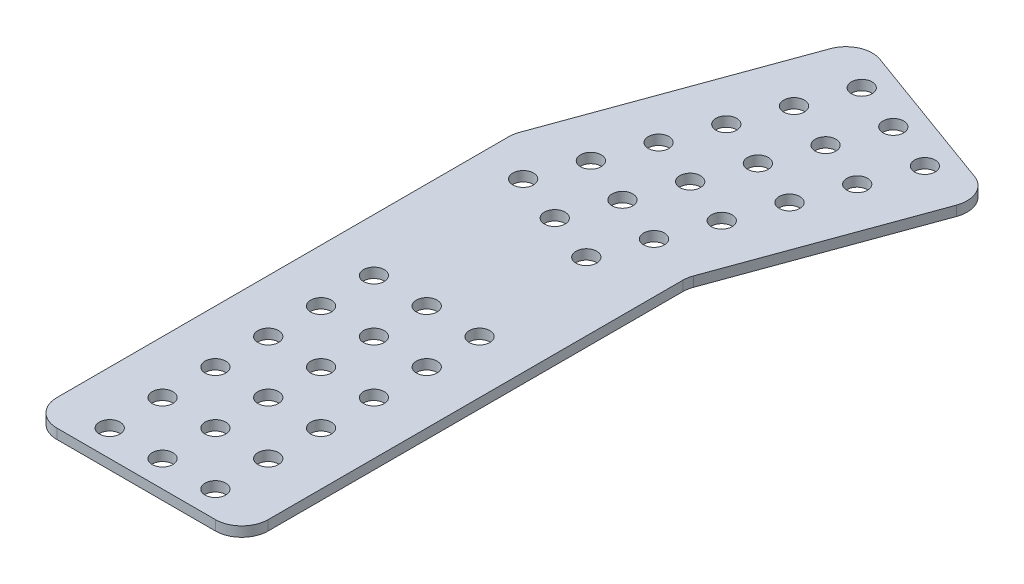
SolidWorks part; units mm, degrees
ref_plane "Front Plane" through (0, 0, 0) normal (0, 0, 1) x (1, 0, 0)
ref_plane "Top Plane" through (0, 0, 0) normal (0, 1, 0) x (1, 0, 0)
ref_plane "Right Plane" through (0, 0, 0) normal (1, 0, 0) x (0, 0, -1)
sketch "Sketch1" plane through (0, 0, 0) normal (0, 1, 0) x (1, 0, 0)
  line L0 (-80.3795, -295.1056) -> (-128.1159, -277.731) construction
  line L1 (-80.3795, -295.1056) -> (128.1159, 277.731) construction
  line L2 (-124.5455, -267.9214) -> (80.3795, 295.1056) construction
  line L3 (128.1159, 277.731) -> (80.3795, 295.1056) construction
  line L4 (-80.3795, -295.1056) -> (80.3795, 295.1056) construction
  line L5 (-128.1159, -277.731) -> (128.1159, 277.731) construction
  line L6 (104.2477, 286.4183) -> (-104.2477, -286.4183) construction
  line L7 (-73.7455, -307.8056) -> (-124.5455, -307.8056)
  line L8 (-73.7455, -307.8056) -> (-73.7455, -422.1056) construction
  line L9 (-73.7455, -422.1056) -> (-124.5455, -422.1056) construction
  line L10 (-124.5455, -307.8056) -> (-124.5455, -422.1056) construction
  line L11 (-99.1455, -307.8056) -> (-99.1455, -422.1056) construction
  line L12 (-105.4955, -307.8056) -> (-105.4955, -422.1056) construction
  line L13 (-99.1455, -307.8056) -> (-99.1455, -288.2754) construction
  line L14 (98.2807, 288.5901) -> (-110.2148, -284.2465) construction
  line L15 (-102.054, -206.1264) -> (-54.3176, -223.501)
  line L16 (-102.054, -206.1264) -> (-124.5455, -267.9214)
  line L19 (-73.7455, -384.0056) -> (-124.5455, -384.0056)
  line L20 (-73.7455, -307.8056) -> (-73.7455, -384.0056)
  line L21 (-124.5455, -307.8056) -> (-124.5455, -384.0056)
  line L22 (-124.5455, -307.8056) -> (-124.5455, -267.9214)
  line L23 (-124.5455, -267.9214) -> (-73.7455, -286.4111)
  line L24 (-73.7455, -307.8056) -> (-73.7455, -286.4111)
  line L26 (-128.1159, -277.731) -> (-124.5455, -307.8056) construction
  line L27 (-73.7455, -286.4111) -> (-73.7455, -276.8788)
  line L28 (-54.3176, -223.501) -> (-73.7455, -276.8788)
  circle A0 centre (-111.8455, -314.1556) radius 2.4892
  circle A1 centre (-111.8455, -326.8556) radius 2.4892
  circle A2 centre (-111.8455, -339.5556) radius 2.4892
  circle A3 centre (-111.8455, -352.2556) radius 2.4892
  circle A4 centre (-111.8455, -364.9556) radius 2.4892
  circle A5 centre (-111.8455, -377.6556) radius 2.4892
  circle A6 centre (-111.8455, -390.3556) radius 2.4892 construction
  circle A7 centre (-111.8455, -403.0556) radius 2.4892 construction
  circle A8 centre (-111.8455, -415.7556) radius 2.4892 construction
  circle A9 centre (-99.1455, -403.0556) radius 2.4892 construction
  circle A10 centre (-99.1455, -390.3556) radius 2.4892 construction
  circle A11 centre (-99.1455, -377.6556) radius 2.4892
  circle A12 centre (-99.1455, -364.9556) radius 2.4892
  circle A13 centre (-99.1455, -352.2556) radius 2.4892
  circle A14 centre (-99.1455, -339.5556) radius 2.4892
  circle A15 centre (-99.1455, -326.8556) radius 2.4892
  circle A16 centre (-99.1455, -314.1556) radius 2.4892
  circle A17 centre (-86.4455, -415.7556) radius 2.4892 construction
  circle A18 centre (-86.4455, -403.0556) radius 2.4892 construction
  circle A19 centre (-86.4455, -390.3556) radius 2.4892 construction
  circle A20 centre (-86.4455, -377.6556) radius 2.4892
  circle A21 centre (-86.4455, -364.9556) radius 2.4892
  circle A22 centre (-86.4455, -352.2556) radius 2.4892
  circle A23 centre (-86.4455, -339.5556) radius 2.4892
  circle A24 centre (-86.4455, -326.8556) radius 2.4892
  circle A25 centre (-86.4455, -314.1556) radius 2.4892
  circle A26 centre (-99.1455, -415.7556) radius 2.4892 construction
  circle A27 centre (90.1418, 284.7949) radius 2.4892 construction
  circle A28 centre (85.7982, 272.8608) radius 2.4892 construction
  circle A29 centre (81.4545, 260.9267) radius 2.4892 construction
  circle A30 centre (77.1108, 248.9926) radius 2.4892 construction
  circle A31 centre (72.7672, 237.0585) radius 2.4892 construction
  circle A32 centre (68.4235, 225.1244) radius 2.4892 construction
  circle A33 centre (64.0799, 213.1903) radius 2.4892 construction
  circle A34 centre (59.7362, 201.2562) radius 2.4892 construction
  circle A35 centre (55.3926, 189.3221) radius 2.4892 construction
  circle A36 centre (51.0489, 177.3881) radius 2.4892 construction
  circle A37 centre (46.7053, 165.454) radius 2.4892 construction
  circle A38 centre (42.3616, 153.5199) radius 2.4892 construction
  circle A39 centre (38.0179, 141.5858) radius 2.4892 construction
  circle A40 centre (33.6743, 129.6517) radius 2.4892 construction
  circle A41 centre (29.3306, 117.7176) radius 2.4892 construction
  circle A42 centre (24.987, 105.7835) radius 2.4892 construction
  circle A43 centre (20.6433, 93.8494) radius 2.4892 construction
  circle A44 centre (16.2997, 81.9153) radius 2.4892 construction
  circle A45 centre (11.956, 69.9812) radius 2.4892 construction
  circle A46 centre (7.6124, 58.0471) radius 2.4892 construction
  circle A47 centre (3.2687, 46.113) radius 2.4892 construction
  circle A48 centre (-1.075, 34.1789) radius 2.4892 construction
  circle A49 centre (-5.4186, 22.2448) radius 2.4892 construction
  circle A50 centre (-9.7623, 10.3107) radius 2.4892 construction
  circle A51 centre (-14.1059, -1.6234) radius 2.4892 construction
  circle A52 centre (-18.4496, -13.5575) radius 2.4892 construction
  circle A53 centre (-22.7932, -25.4916) radius 2.4892 construction
  circle A54 centre (-27.1369, -37.4257) radius 2.4892 construction
  circle A55 centre (-31.4805, -49.3598) radius 2.4892 construction
  circle A56 centre (-35.8242, -61.2939) radius 2.4892 construction
  circle A57 centre (-40.1679, -73.228) radius 2.4892 construction
  circle A58 centre (-44.5115, -85.1621) radius 2.4892 construction
  circle A59 centre (-48.8552, -97.0962) radius 2.4892 construction
  circle A60 centre (-53.1988, -109.0303) radius 2.4892 construction
  circle A61 centre (-57.5425, -120.9644) radius 2.4892 construction
  circle A62 centre (-61.8861, -132.8985) radius 2.4892 construction
  circle A63 centre (-66.2298, -144.8325) radius 2.4892 construction
  circle A64 centre (-70.5734, -156.7666) radius 2.4892 construction
  circle A65 centre (-74.9171, -168.7007) radius 2.4892 construction
  circle A66 centre (-79.2608, -180.6348) radius 2.4892 construction
  circle A67 centre (-83.6044, -192.5689) radius 2.4892 construction
  circle A68 centre (-87.9481, -204.503) radius 2.4892 construction
  circle A69 centre (-92.2917, -216.4371) radius 2.4892
  circle A70 centre (-96.6354, -228.3712) radius 2.4892
  circle A71 centre (-100.979, -240.3053) radius 2.4892
  circle A72 centre (-105.3227, -252.2394) radius 2.4892
  circle A73 centre (-109.6664, -264.1735) radius 2.4892
  circle A74 centre (-114.01, -276.1076) radius 2.4892
  circle A75 centre (62.983, 173.0444) radius 2.4892 construction
  circle A76 centre (67.3267, 184.9785) radius 2.4892 construction
  circle A77 centre (71.6703, 196.9126) radius 2.4892 construction
  circle A78 centre (76.014, 208.8467) radius 2.4892 construction
  circle A79 centre (80.3576, 220.7808) radius 2.4892 construction
  circle A80 centre (84.7013, 232.7149) radius 2.4892 construction
  circle A81 centre (89.0449, 244.649) radius 2.4892 construction
  circle A82 centre (93.3886, 256.5831) radius 2.4892 construction
  circle A83 centre (97.7323, 268.5172) radius 2.4892 construction
  circle A84 centre (102.0759, 280.4513) radius 2.4892 construction
  circle A85 centre (-102.0759, -280.4513) radius 2.4892
  circle A86 centre (-97.7323, -268.5172) radius 2.4892
  circle A87 centre (-93.3886, -256.5831) radius 2.4892
  circle A88 centre (-89.0449, -244.649) radius 2.4892
  circle A89 centre (-84.7013, -232.7149) radius 2.4892
  circle A90 centre (-80.3576, -220.7808) radius 2.4892
  circle A91 centre (-76.014, -208.8467) radius 2.4892 construction
  circle A92 centre (-71.6703, -196.9126) radius 2.4892 construction
  circle A93 centre (-67.3267, -184.9785) radius 2.4892 construction
  circle A94 centre (-62.983, -173.0444) radius 2.4892 construction
  circle A95 centre (-58.6394, -161.1103) radius 2.4892 construction
  circle A96 centre (-54.2957, -149.1762) radius 2.4892 construction
  circle A97 centre (-49.952, -137.2421) radius 2.4892 construction
  circle A98 centre (-45.6084, -125.308) radius 2.4892 construction
  circle A99 centre (-41.2647, -113.3739) radius 2.4892 construction
  circle A100 centre (-36.9211, -101.4398) radius 2.4892 construction
  circle A101 centre (-32.5774, -89.5057) radius 2.4892 construction
  circle A102 centre (-28.2338, -77.5716) radius 2.4892 construction
  circle A103 centre (-23.8901, -65.6375) radius 2.4892 construction
  circle A104 centre (-19.5465, -53.7034) radius 2.4892 construction
  circle A105 centre (-15.2028, -41.7693) radius 2.4892 construction
  circle A106 centre (-10.8591, -29.8352) radius 2.4892 construction
  circle A107 centre (-6.5155, -17.9011) radius 2.4892 construction
  circle A108 centre (-2.1718, -5.967) radius 2.4892 construction
  circle A109 centre (2.1718, 5.967) radius 2.4892 construction
  circle A110 centre (6.5155, 17.9011) radius 2.4892 construction
  circle A111 centre (10.8591, 29.8352) radius 2.4892 construction
  circle A112 centre (15.2028, 41.7693) radius 2.4892 construction
  circle A113 centre (19.5465, 53.7034) radius 2.4892 construction
  circle A114 centre (23.8901, 65.6375) radius 2.4892 construction
  circle A115 centre (28.2338, 77.5716) radius 2.4892 construction
  circle A116 centre (32.5774, 89.5057) radius 2.4892 construction
  circle A117 centre (36.9211, 101.4398) radius 2.4892 construction
  circle A118 centre (41.2647, 113.3739) radius 2.4892 construction
  circle A119 centre (45.6084, 125.308) radius 2.4892 construction
  circle A120 centre (49.952, 137.2421) radius 2.4892 construction
  circle A121 centre (54.2957, 149.1762) radius 2.4892 construction
  circle A122 centre (58.6394, 161.1103) radius 2.4892 construction
  circle A123 centre (-90.1418, -284.7949) radius 2.4892
  circle A124 centre (-85.7982, -272.8608) radius 2.4892
  circle A125 centre (-81.4545, -260.9267) radius 2.4892
  circle A126 centre (-77.1108, -248.9926) radius 2.4892
  circle A127 centre (-72.7672, -237.0585) radius 2.4892
  circle A128 centre (-68.4235, -225.1244) radius 2.4892
  circle A129 centre (-64.0799, -213.1903) radius 2.4892 construction
  circle A130 centre (-59.7362, -201.2562) radius 2.4892 construction
  circle A131 centre (-55.3926, -189.3221) radius 2.4892 construction
  circle A132 centre (-51.0489, -177.3881) radius 2.4892 construction
  circle A133 centre (-46.7053, -165.454) radius 2.4892 construction
  circle A134 centre (-42.3616, -153.5199) radius 2.4892 construction
  circle A135 centre (-38.0179, -141.5858) radius 2.4892 construction
  circle A136 centre (-33.6743, -129.6517) radius 2.4892 construction
  circle A137 centre (-29.3306, -117.7176) radius 2.4892 construction
  circle A138 centre (-24.987, -105.7835) radius 2.4892 construction
  circle A139 centre (-20.6433, -93.8494) radius 2.4892 construction
  circle A140 centre (-16.2997, -81.9153) radius 2.4892 construction
  circle A141 centre (-11.956, -69.9812) radius 2.4892 construction
  circle A142 centre (-7.6124, -58.0471) radius 2.4892 construction
  circle A143 centre (-3.2687, -46.113) radius 2.4892 construction
  circle A144 centre (1.075, -34.1789) radius 2.4892 construction
  circle A145 centre (5.4186, -22.2448) radius 2.4892 construction
  circle A146 centre (9.7623, -10.3107) radius 2.4892 construction
  circle A147 centre (14.1059, 1.6234) radius 2.4892 construction
  circle A148 centre (18.4496, 13.5575) radius 2.4892 construction
  circle A149 centre (22.7932, 25.4916) radius 2.4892 construction
  circle A150 centre (27.1369, 37.4257) radius 2.4892 construction
  circle A151 centre (31.4805, 49.3598) radius 2.4892 construction
  circle A152 centre (35.8242, 61.2939) radius 2.4892 construction
  circle A153 centre (40.1679, 73.228) radius 2.4892 construction
  circle A154 centre (44.5115, 85.1621) radius 2.4892 construction
  circle A155 centre (48.8552, 97.0962) radius 2.4892 construction
  circle A156 centre (53.1988, 109.0303) radius 2.4892 construction
  circle A157 centre (57.5425, 120.9644) radius 2.4892 construction
  circle A158 centre (61.8861, 132.8985) radius 2.4892 construction
  circle A159 centre (66.2298, 144.8325) radius 2.4892 construction
  circle A160 centre (70.5734, 156.7666) radius 2.4892 construction
  circle A161 centre (74.9171, 168.7007) radius 2.4892 construction
  circle A162 centre (79.2608, 180.6348) radius 2.4892 construction
  circle A163 centre (83.6044, 192.5689) radius 2.4892 construction
  circle A164 centre (87.9481, 204.503) radius 2.4892 construction
  circle A165 centre (92.2917, 216.4371) radius 2.4892 construction
  circle A166 centre (96.6354, 228.3712) radius 2.4892 construction
  circle A167 centre (100.979, 240.3053) radius 2.4892 construction
  circle A168 centre (105.3227, 252.2394) radius 2.4892 construction
  circle A169 centre (109.6664, 264.1735) radius 2.4892 construction
  circle A170 centre (114.01, 276.1076) radius 2.4892 construction
  point P1 (0, 0)
  dimension "D9" = 4.9784
  dimension "D15" = 4.9784
  dimension "D1" = 50.8
  dimension "D2" = 609.6
  dimension "D3" = 50.8
  dimension "D4" = 114.3
  dimension "D5" = 20
  dimension "D6" = 12.7
  dimension "D7" = 30.2858
  dimension "D8" = 6.35
  dimension "D10" = 6.35
  dimension "D11" = 12.7
  dimension "D13" = 12.7
  dimension "D14" = 6.35
  dimension "D16" = 6.35
  dimension "D17" = 12.7
  dimension "D19" = 12.7
  dimension "D20" = 6.35
  dimension "D21" = 6.35
  dimension "D12" = 9
  dimension "D18" = 48
extrude "Boss-Extrude1" add sketch "Sketch1" along normal blind 2.3813
fillet "Fillet1" radius 6.35 6 edges at (-54.3176, 1.1906, 223.501) (-102.054, 1.1906, 206.1264) (-124.5455, 1.1906, 267.9214) (-73.7455, 1.1906, 276.8788) (-73.7455, 1.1906, 384.0056) (-124.5455, 1.1906, 384.0056)
